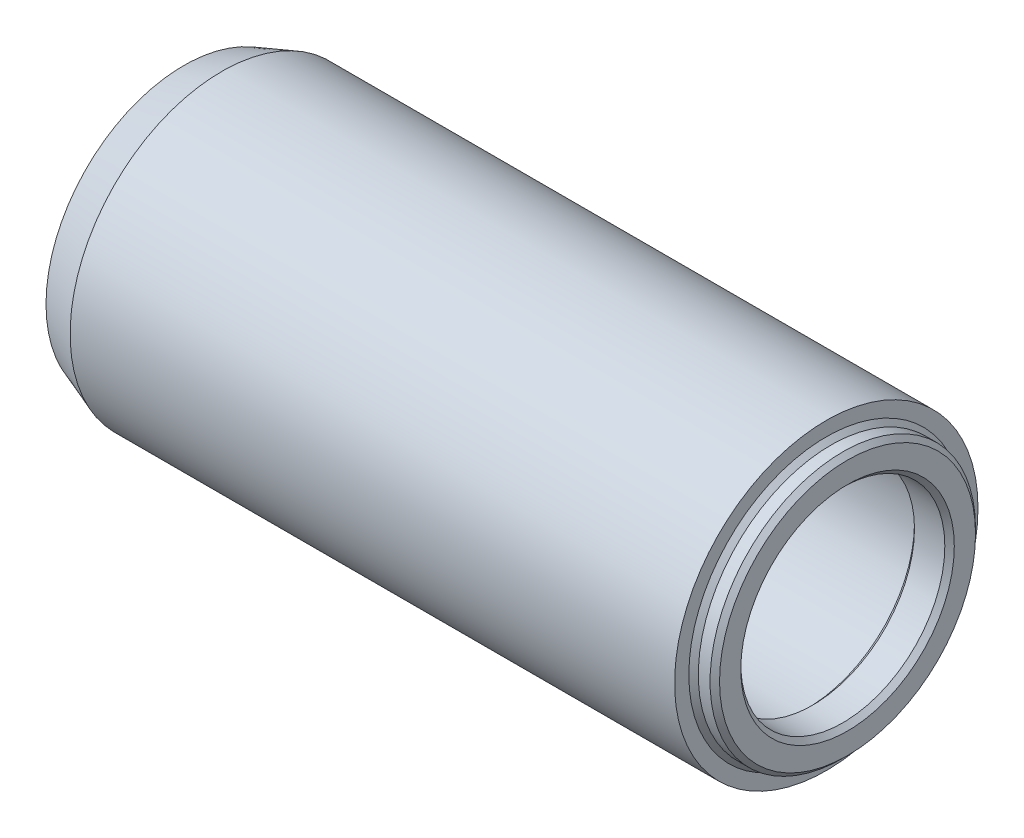
SolidWorks part; units mm, degrees
material "1.0037 (S235JR)"
ref_plane "Alzado" through (0, 0, 0) normal (0, 0, 1) x (1, 0, 0)
ref_plane "Planta" through (0, 0, 0) normal (0, 1, 0) x (1, 0, 0)
ref_plane "Vista lateral" through (0, 0, 0) normal (1, 0, 0) x (0, 0, -1)
sketch "Sketch1" plane through (0, 0, 0) normal (0, 0, 1) x (1, 0, 0)
  line L0 (0, 0) -> (-53, 0) construction
  line L1 (-33.8775, 7.2721) -> (-31.8775, 8)
  line L2 (0, 8) -> (0, 7)
  line L3 (0, 7) -> (1.12, 7)
  line L11 (1.12, 7) -> (1.12, 5.3805)
  line L19 (0, 8) -> (-31.8775, 8)
  line L21 (-33.8775, 7.2721) -> (-33.8775, 6)
  line L22 (-33.8775, 6) -> (-0.9798, 6)
  line L23 (-0.9798, 6) -> (-0.9798, 5.3805)
  line L24 (-0.9798, 5.3805) -> (0, 5.3805)
  line L25 (1.12, 5.3805) -> (0, 5.3805)
  line L26 (0, 0) -> (5.8547, 0) construction
  point P9 (-19.4354, 8)
  point P15 (-31.8475, 8)
  dimension "D1" = 8
  dimension "D3" = 6
  dimension "D4" = 7
  dimension "D5" = 20
  dimension "D6" = 2
  dimension "D7" = 5.3805
revolve "Revolve1" add sketch "Sketch1" angle 360 about L0
chamfer "Chaflán10" distance 0.25 angle 45 5 edges at (-0.9798, 0, -5.3805) (-33.8775, 0, -6) (0, 0, -7) (1.12, 0, -5.3805) (1.12, 0, -7)
fillet "Fillet1" radius 0.25 1 edges at (-0.9798, 0, -6)
